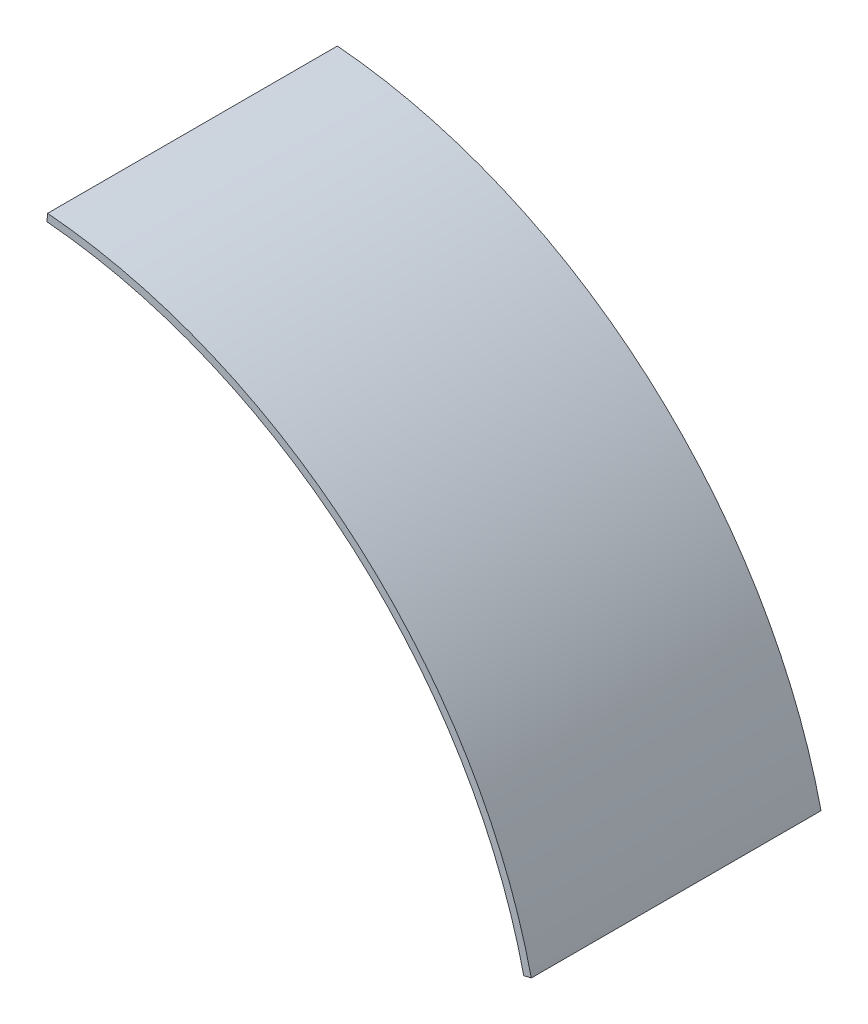
SolidWorks part; units mm, degrees
ref_plane "前视基准面" through (0, 0, 0) normal (0, 0, 1) x (1, 0, 0)
ref_plane "上视基准面" through (0, 0, 0) normal (0, 1, 0) x (1, 0, 0)
ref_plane "右视基准面" through (0, 0, 0) normal (1, 0, 0) x (0, 0, -1)
sketch "草图1" plane through (0, 0, 0) normal (0, 0, 1) x (1, 0, 0)
  line L0 (0, 0) -> (61.054, 702.3513) construction
  line L1 (0, 0) -> (687.019, 158.2083) construction
  line L4 (0, 705) -> (0, 680)
  line L5 (673.3823, 94.6377) -> (698.139, 98.117)
  line L7 (61.054, 702.3513) -> (60.188, 692.3889)
  line L8 (687.019, 158.2083) -> (677.2741, 155.9642)
  arc A0 (698.139, 98.117) -> (0, 705) centre (0, 0) ccw construction
  arc A1 (60.188, 692.3889) -> (677.2741, 155.9642) centre (0, 0) cw
  arc A3 (698.139, 98.117) -> (0, 705) centre (0, 0) ccw
  arc A4 (673.3823, 94.6377) -> (0, 680) centre (0, 0) ccw
  arc A5 (687.019, 158.2083) -> (61.054, 702.3513) centre (0, 0) ccw
  dimension "D3" = 72.064
  dimension "D1" = 0
  dimension "D2" = 10
extrude "凸台-拉伸1" add sketch "草图1" against normal blind 375
sketch "草图2" plane through (0, 0, -375) normal (0, 0, -1) x (-1, 0, 0)
  line L0 (0, 0) -> (-462.5216, 532.0703) construction
  arc A0 (-61.054, 702.3513) -> (-687.019, 158.2083) centre (0, 0) ccw construction
